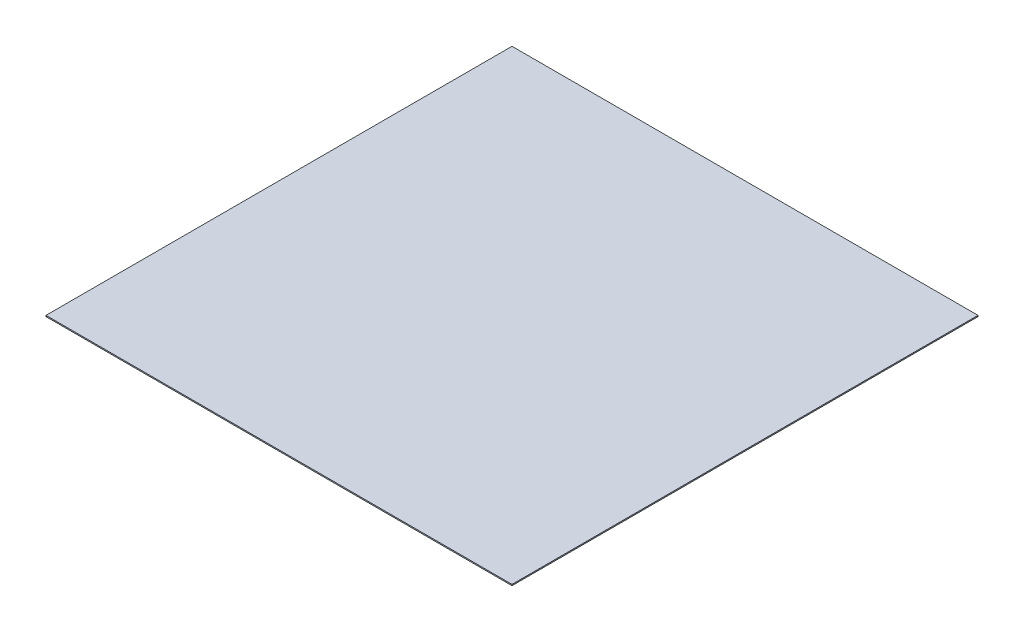
SolidWorks part; units mm, degrees
ref_plane "Front Plane" through (0, 0, 0) normal (0, 0, 1) x (1, 0, 0)
ref_plane "Top Plane" through (0, 0, 0) normal (0, 1, 0) x (1, 0, 0)
ref_plane "Right Plane" through (0, 0, 0) normal (1, 0, 0) x (0, 0, -1)
sketch "Sketch1" plane through (0, 0, 0) normal (0, 1, 0) x (1, 0, 0)
  line L1 (-200, -200) -> (200, -200)
  line L2 (-200, -200) -> (-200, 200)
  line L3 (-200, 200) -> (200, 200)
  line L4 (200, -200) -> (200, 200)
  line L5 (-200, -200) -> (200, 200) construction
  line L6 (-200, 200) -> (200, -200) construction
  point P0 (0, 0)
  dimension "D1" = 400
  dimension "D2" = 400
extrude "Boss-Extrude1" add sketch "Sketch1" along normal blind 1
